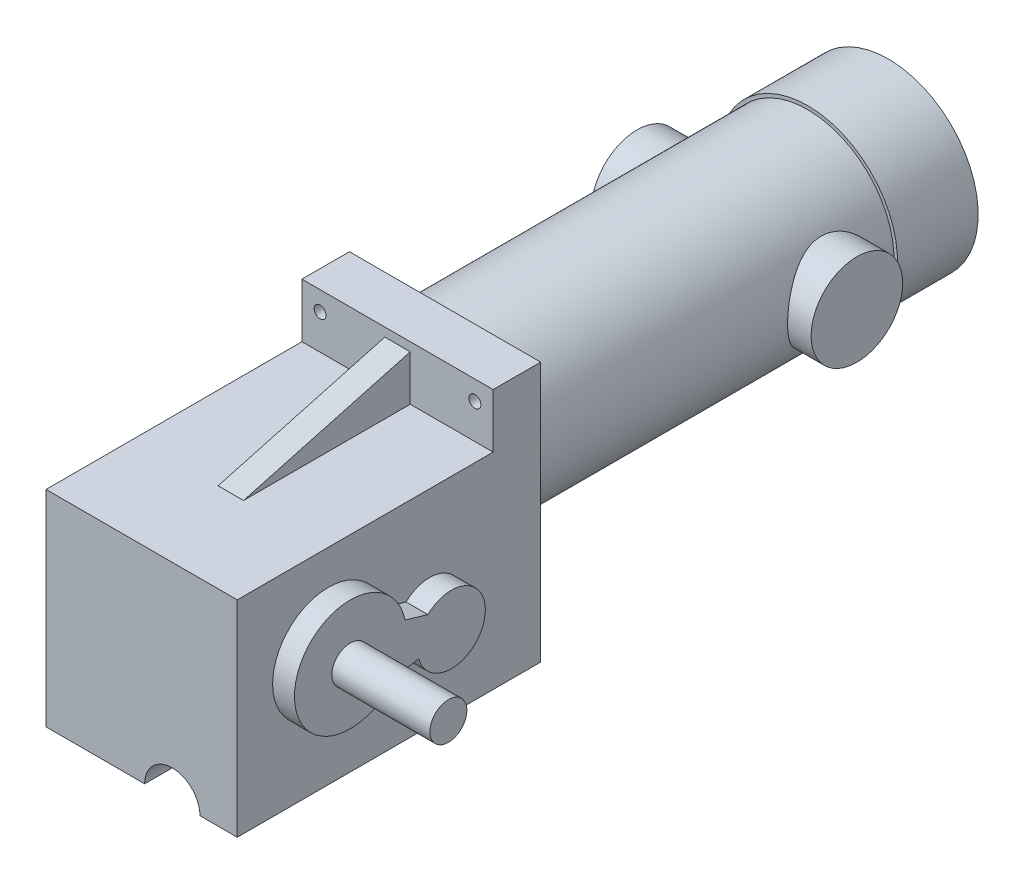
SolidWorks part; units mm, degrees
ref_plane "Front Plane" through (0, 0, 0) normal (0, 0, 1) x (1, 0, 0)
ref_plane "Top Plane" through (0, 0, 0) normal (0, 1, 0) x (1, 0, 0)
ref_plane "Right Plane" through (0, 0, 0) normal (1, 0, 0) x (0, 0, -1)
ref_plane "Plane1" through (0, 0, -41.91) normal (0, 0, 1) x (1, 0, 0)
sketch "Sketch1" plane through (0, 0, 0) normal (0, 0, 1) x (1, 0, 0)
  line L1 (43.942, 47.244) -> (-43.942, 47.244)
  line L2 (43.942, 47.244) -> (43.942, -47.244)
  line L3 (43.942, -47.244) -> (-43.942, -47.244)
  line L4 (-43.942, 47.244) -> (-43.942, -47.244)
  line L5 (43.942, 47.244) -> (-43.942, -47.244) construction
  line L6 (43.942, -47.244) -> (-43.942, 47.244) construction
  point P0 (0, 0)
  dimension "D1" = 87.884
  dimension "D2" = 94.488
extrude "Boss-Extrude1" add sketch "Sketch1" against normal blind 139.446
sketch "Sketch2" plane through (43.942, 0, 0) normal (1, 0, 0) x (0, 0, -1)
  line L0 (139.446, -47.244) -> (0, -47.244) construction
  line L2 (41.91, 69.0118) -> (41.91, -69.0118) construction
  circle A0 centre (41.91, 5.6388) radius 8.5
  dimension "D3" = 17
  dimension "D1" = 52.8828
extrude "Boss-Extrude2" add sketch "Sketch2" along normal blind 55.118
sketch "Sketch3" plane through (0, 0, -139.446) normal (0, 0, -1) x (-1, 0, 0)
  line L0 (43.942, -47.244) -> (-43.942, -47.244) construction
  circle A0 centre (0, 27.686) radius 39.6875
  dimension "D1" = 79.375
  dimension "D2" = 74.93
extrude "Boss-Extrude3" add sketch "Sketch3" along normal blind 176.022
sketch "Sketch4" plane through (0, 0, -139.446) normal (0, 0, 1) x (1, 0, 0)
  line L0 (43.942, 47.244) -> (-43.942, 47.244) construction
  line L1 (-43.942, 72.136) -> (43.942, 72.136)
  line L2 (-43.942, 72.136) -> (-43.942, 47.244)
  line L3 (43.942, 47.244) -> (-43.942, 47.244)
  line L4 (43.942, 72.136) -> (43.942, 47.244)
  line L5 (-43.942, -47.244) -> (43.942, -47.244) construction
  point P0 (0, 27.686)
  point P1 (0, 27.686)
  dimension "D1" = 119.38
extrude "Boss-Extrude4" add sketch "Sketch4" along normal blind 21.844
sketch "Sketch5" plane through (0, 0, 0) normal (1, 0, 0) x (0, 0, -1)
  line L0 (41.0006, 47.244) -> (117.602, 68.1184)
  line L1 (117.602, 47.244) -> (0, 47.244) construction
  line L3 (117.602, 47.244) -> (117.602, 68.1184)
  line L4 (117.602, 47.244) -> (41.0006, 47.244)
  line L5 (117.602, 47.244) -> (117.602, 72.136) construction
extrude "Boss-Extrude5" add sketch "Sketch5" along normal mid plane 11.684
sketch "Sketch6" plane through (43.942, 0, 0) normal (1, 0, 0) x (0, 0, -1)
  line L0 (67.0628, 10.6851) -> (77.5828, 7.6054)
  line L1 (73.3188, -7.886) -> (62.5178, -9.6401)
  arc A0 (67.0628, 10.6851) -> (62.5178, -9.6401) centre (41.91, 5.6388) ccw
  arc A1 (73.3188, -7.886) -> (77.5828, 7.6054) centre (88.3672, -3.6956) ccw
  dimension "D1" = 51.308
  dimension "D2" = 31.242
extrude "not verified extrude" add sketch "Sketch6" along normal blind 10.033
sketch "Sketch8" plane through (0, 0, -139.446) normal (0, 0, -1) x (-1, 0, 0)
  line L1 (35.56, -7.874) -> (-35.56, -7.874) construction
  line L2 (35.56, -7.874) -> (35.56, 63.246) construction
  line L3 (35.56, 63.246) -> (-35.56, 63.246) construction
  line L4 (-35.56, -7.874) -> (-35.56, 63.246) construction
  line L5 (35.56, -7.874) -> (-35.56, 63.246) construction
  line L6 (35.56, 63.246) -> (-35.56, -7.874) construction
  circle A0 centre (-35.56, 63.246) radius 2.75
  circle A1 centre (35.56, 63.246) radius 2.75
  circle A2 centre (35.56, -7.874) radius 2.75
  circle A3 centre (-35.56, -7.874) radius 2.75
  point P0 (0, 27.686)
  point P1 (0, 27.686)
  dimension "D1" = 5.5
  dimension "D2" = 71.12
  dimension "D3" = 71.12
extrude "Cut-Extrude2" cut sketch "Sketch8" against normal blind 25.4
sketch "Sketch7" plane through (0, 0, 0) normal (0, 0, 1) x (1, 0, 0)
  line L0 (-43.942, -47.244) -> (43.942, -47.244) construction
  line L2 (53.975, -20.0152) -> (53.975, 31.2928) construction
  circle A0 centre (14.097, -47.244) radius 12.7
  dimension "D1" = 25.4
  dimension "D2" = 39.878
extrude "change for opposite motor" cut sketch "Sketch7" against normal through all
sketch "Sketch9" plane through (0, -47.244, 0) normal (0, -1, 0) x (1, 0, 0)
  line L0 (53.975, -67.0628) -> (53.975, -16.256) construction
  line L1 (26.797, 0) -> (1.397, 0) construction
  circle A0 centre (-8.001, -7.9756) radius 3
  circle A1 centre (-8.001, -68.3768) radius 3
  circle A2 centre (-8.001, -128.778) radius 3
  circle A3 centre (36.449, -128.778) radius 3
  circle A4 centre (36.449, -68.3768) radius 3
  circle A5 centre (36.449, -7.9756) radius 3
  dimension "D5" = 6
  dimension "D1" = 61.976
  dimension "D2" = 60.4012
  dimension "D3" = 60.4012
  dimension "D4" = 7.9756
  dimension "D6" = 44.45
extrude "Cut-Extrude3" cut sketch "Sketch9" against normal blind 12.7
sketch "Sketch10" plane through (0, -47.244, 0) normal (0, -1, 0) x (1, 0, 0)
  line L0 (53.975, -67.0628) -> (53.975, -16.256) construction
  line L1 (-43.942, 0) -> (1.397, 0) construction
  circle A0 centre (-32.639, -31.496) radius 8.5725
  circle A1 centre (-32.639, -104.4448) radius 8.5725
  dimension "D1" = 17.145
  dimension "D2" = 86.614
  dimension "D3" = 31.496
  dimension "D4" = 72.9488
extrude "Boss-Extrude6" add sketch "Sketch10" along normal blind 6.096
sketch "Sketch14" plane through (0, 0, -315.468) normal (0, 0, -1) x (-1, 0, 0)
  line L0 (-26.5, 27.686) -> (26.5, 27.686) construction
  circle A0 centre (-26.5, 27.686) radius 1.5
  circle A1 centre (26.5, 27.686) radius 1.5
  point P0 (0, 27.686)
  point P5 (0, 27.686)
  dimension "D2" = 3
  dimension "D1" = 53
extrude "Cut-Extrude4" cut sketch "Sketch14" against normal blind 25.4
sketch "Sketch11" plane through (-43.942, 0, 0) normal (-1, 0, 0) x (0, 0, 1)
  line L0 (-77.5828, 7.6054) -> (-67.0628, 10.6851) construction
  line L1 (-62.5178, -9.6401) -> (-73.3188, -7.886) construction
  line L2 (-77.5828, 7.6054) -> (-67.0628, 10.6851)
  line L3 (-62.5178, -9.6401) -> (-73.3188, -7.886)
  arc A0 (-62.5178, -9.6401) -> (-67.0628, 10.6851) centre (-41.91, 5.6388) ccw construction
  arc A1 (-77.5828, 7.6054) -> (-73.3188, -7.886) centre (-88.3672, -3.6956) ccw construction
  circle A2 centre (-41.91, 5.6388) radius 8.5 construction
  arc A3 (-62.5178, -9.6401) -> (-67.0628, 10.6851) centre (-41.91, 5.6388) ccw
  arc A4 (-77.5828, 7.6054) -> (-73.3188, -7.886) centre (-88.3672, -3.6956) ccw
  circle A5 centre (-41.91, 5.6388) radius 8.5
extrude "Boss-Extrude7" add sketch "Sketch11" along normal blind 9.398
sketch "Sketch12" plane through (0, 0, 0) normal (1, 0, 0) x (0, 0, -1)
  line L0 (315.468, 27.686) -> (278.2125, 26.9725) construction
  line L1 (315.468, -12.0015) -> (315.468, 67.3735) construction
  circle A0 centre (278.2125, 26.9725) radius 21.0269
  dimension "D3" = 42.0538
  dimension "D1" = 37.2555
  dimension "D2" = 88.903
extrude "Boss-Extrude8" add sketch "Sketch12" along normal mid plane 100.965
sketch "Sketch13" plane through (0, 0, -315.468) normal (0, 0, -1) x (-1, 0, 0)
  line L1 (-7.493, 35.179) -> (7.493, 35.179)
  line L2 (-7.493, 35.179) -> (-7.493, 20.193)
  line L3 (-7.493, 20.193) -> (7.493, 20.193)
  line L4 (7.493, 35.179) -> (7.493, 20.193)
  line L5 (-7.493, 35.179) -> (7.493, 20.193) construction
  line L6 (-7.493, 20.193) -> (7.493, 35.179) construction
  point P0 (0, 27.686)
  dimension "D1" = 14.986
extrude "Boss-Extrude9" add sketch "Sketch13" along normal blind 6.35
sketch "Sketch15" plane through (0, 0, -315.468) normal (0, 0, -1) x (-1, 0, 0)
  circle A0 centre (0, 27.686) radius 41.275
  dimension "D1" = 82.55
extrude "brake and end cap" add sketch "Sketch15" along normal blind 27.686 and the other way blind 9.398
